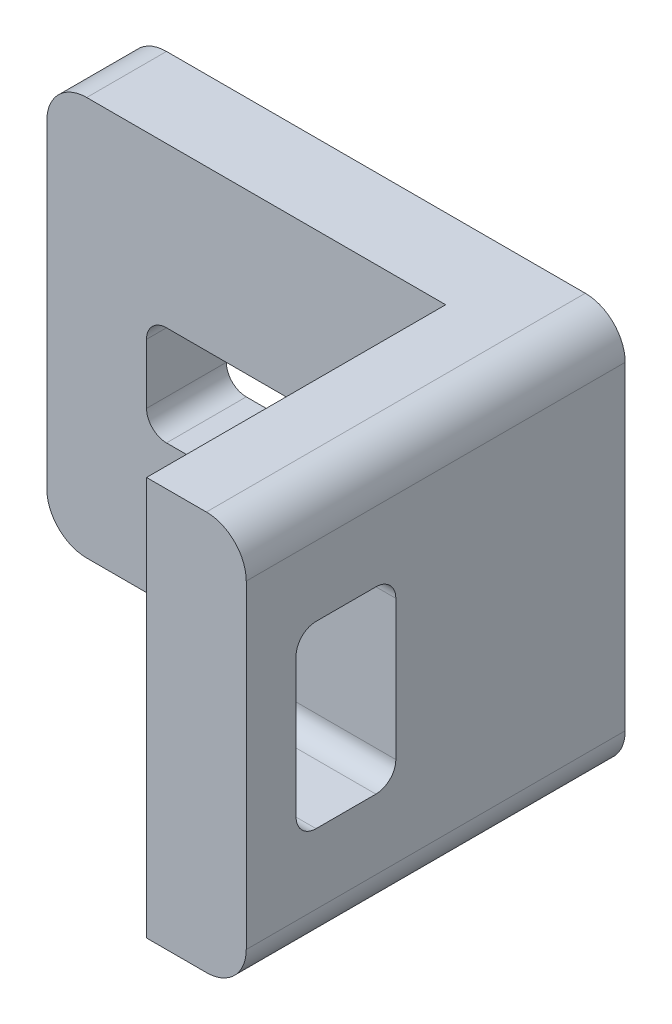
SolidWorks part; units mm, degrees
ref_plane "Plan de face" through (0, 0, 0) normal (0, 0, 1) x (1, 0, 0)
ref_plane "Plan de dessus" through (0, 0, 0) normal (0, 1, 0) x (1, 0, 0)
ref_plane "Plan de droite" through (0, 0, 0) normal (1, 0, 0) x (0, 0, -1)
sketch "Esquisse1" plane through (0, 0, 0) normal (0, 0, 1) x (1, 0, 0)
  line L1 (-11.2733, 8.7087) -> (9.7267, 8.7087)
  line L2 (-13.2733, 6.7087) -> (-13.2733, -9.2913)
  line L3 (-11.2733, -11.2913) -> (9.7267, -11.2913)
  line L4 (11.7267, 6.7087) -> (11.7267, -9.2913)
  arc A0 (9.7267, 8.7087) -> (11.7267, 6.7087) centre (9.7267, 6.7087) cw
  arc A1 (11.7267, -9.2913) -> (9.7267, -11.2913) centre (9.7267, -9.2913) cw
  arc A2 (-11.2733, -11.2913) -> (-13.2733, -9.2913) centre (-11.2733, -9.2913) cw
  arc A3 (-13.2733, 6.7087) -> (-11.2733, 8.7087) centre (-11.2733, 6.7087) cw
  point P8 (11.7267, -11.2913)
  point P11 (-13.2733, -11.2913)
  point P14 (-13.2733, 8.7087)
  dimension "D3" = 2
  dimension "D1" = 20
  dimension "D2" = 25
extrude "Boss.-Extru.1" add sketch "Esquisse1" along normal blind 4
sketch "Esquisse2" plane through (0, 0, 4) normal (0, 0, 1) x (1, 0, 0)
  line L1 (6.7267, 8.7087) -> (9.7267, 8.7087)
  line L2 (6.7267, 8.7087) -> (6.7267, -11.2913)
  line L3 (6.7267, -11.2913) -> (9.7267, -11.2913)
  line L4 (11.7267, 6.7087) -> (11.7267, -9.2913)
  line L5 (11.7267, -9.2913) -> (11.7267, 6.7087) construction
  line L6 (9.7267, 8.7087) -> (-11.2733, 8.7087) construction
  line L7 (-11.2733, -11.2913) -> (9.7267, -11.2913) construction
  arc A0 (9.7267, 8.7087) -> (11.7267, 6.7087) centre (9.7267, 6.7087) cw
  arc A1 (11.7267, -9.2913) -> (9.7267, -11.2913) centre (9.7267, -9.2913) cw
  dimension "D1" = 2
  dimension "D2" = 3
extrude "Boss.-Extru.3" add sketch "Esquisse2" along normal blind 15
sketch "Esquisse3" plane through (0, 0, 4) normal (0, 0, 1) x (1, 0, 0)
  line L0 (-13.2733, 6.7087) -> (-13.2733, -9.2913) construction
  line L1 (-7.2733, 0.7087) -> (-0.2733, 0.7087)
  line L2 (-8.2733, -0.2913) -> (-8.2733, -3.2913)
  line L3 (-7.2733, -4.2913) -> (-0.2733, -4.2913)
  line L4 (0.7267, -0.2913) -> (0.7267, -3.2913)
  line L5 (-8.2733, 0.7087) -> (0.7267, -4.2913) construction
  line L6 (-8.2733, -4.2913) -> (0.7267, 0.7087) construction
  line L7 (-11.2733, -11.2913) -> (6.7267, -11.2913) construction
  line L8 (6.7267, 8.7087) -> (-11.2733, 8.7087) construction
  arc A0 (-8.2733, -0.2913) -> (-7.2733, 0.7087) centre (-7.2733, -0.2913) cw
  arc A1 (-8.2733, -3.2913) -> (-7.2733, -4.2913) centre (-7.2733, -3.2913) ccw
  arc A2 (-0.2733, -4.2913) -> (0.7267, -3.2913) centre (-0.2733, -3.2913) ccw
  arc A3 (0.7267, -0.2913) -> (-0.2733, 0.7087) centre (-0.2733, -0.2913) ccw
  point P0 (-3.7733, -1.7913)
  dimension "D4" = 1
  dimension "D1" = 9
  dimension "D2" = 5
  dimension "D3" = 5
  dimension "D5" = 7
  dimension "D6" = 8
extrude "Enlèv. mat.-Extru.1" cut sketch "Esquisse3" against normal blind 50
sketch "Esquisse4" plane through (6.7267, 0, 0) normal (-1, 0, 0) x (0, 0, 1)
  line L0 (12.5, 3.2087) -> (15.5, 3.2087)
  line L1 (11.5, 2.2087) -> (11.5, -4.7913)
  line L2 (12.5, -5.7913) -> (15.5, -5.7913)
  line L3 (16.5, 2.2087) -> (16.5, -4.7913)
  line L4 (19, 8.7087) -> (4, 8.7087) construction
  line L7 (4, 8.7087) -> (4, -11.2913) construction
  arc A0 (11.5, 2.2087) -> (12.5, 3.2087) centre (12.5, 2.2087) cw
  arc A1 (11.5, -4.7913) -> (12.5, -5.7913) centre (12.5, -4.7913) ccw
  arc A2 (15.5, -5.7913) -> (16.5, -4.7913) centre (15.5, -4.7913) ccw
  arc A3 (16.5, 2.2087) -> (15.5, 3.2087) centre (15.5, 2.2087) ccw
  dimension "D1" = 5
  dimension "D2" = 5.5
  dimension "D3" = 9
  dimension "D4" = 7.5
extrude "Enlèv. mat.-Extru.2" cut sketch "Esquisse4" against normal blind 50
